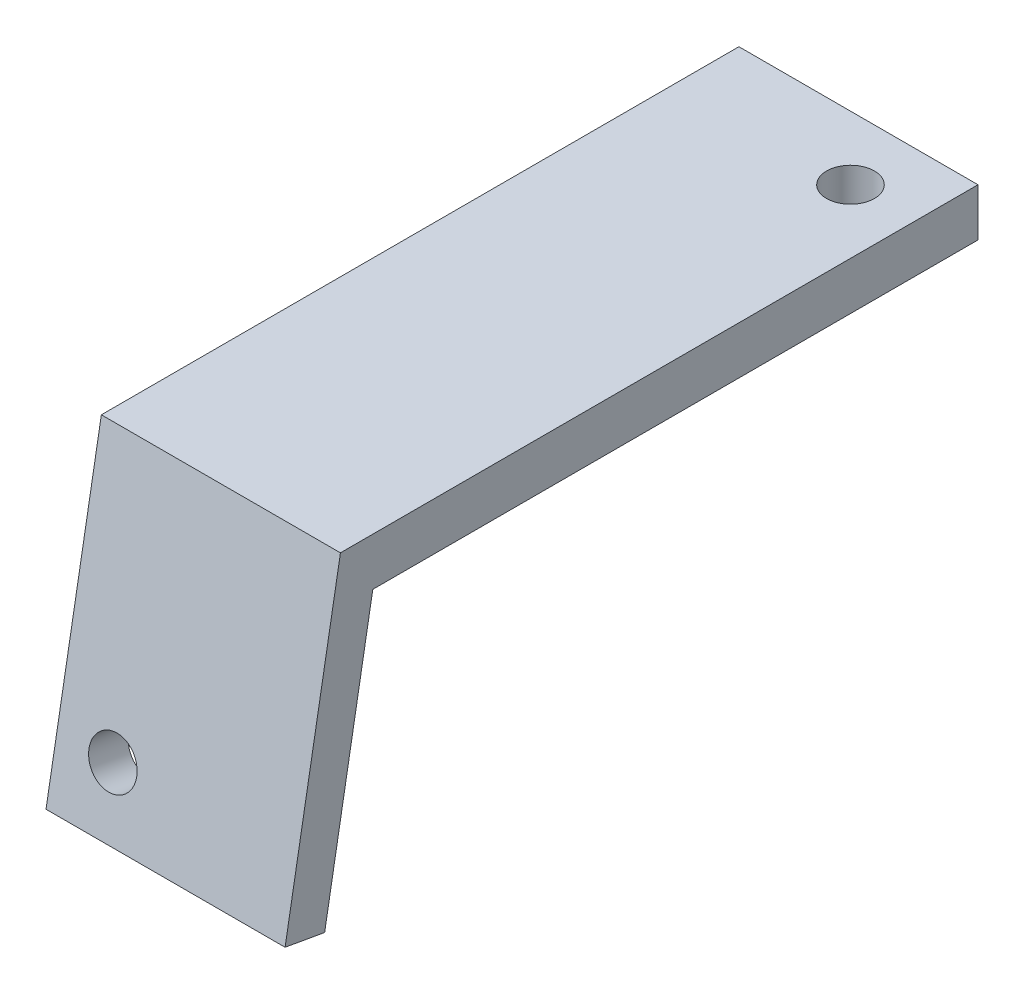
SolidWorks part; units mm, degrees
ref_plane "Front Plane" through (0, 0, 0) normal (0, 0, 1) x (1, 0, 0)
ref_plane "Top Plane" through (0, 0, 0) normal (0, 1, 0) x (1, 0, 0)
ref_plane "Right Plane" through (0, 0, 0) normal (1, 0, 0) x (0, 0, -1)
sketch "Sketch1" plane through (0, 0, 0) normal (0, 1, 0) x (1, 0, 0)
  line L1 (-7.5, -20) -> (7.5, -20)
  line L2 (-7.5, -20) -> (-7.5, 20)
  line L3 (-7.5, 20) -> (7.5, 20)
  line L4 (7.5, -20) -> (7.5, 20)
  line L5 (-7.5, -20) -> (7.5, 20) construction
  line L6 (-7.5, 20) -> (7.5, -20) construction
  circle A0 centre (3.5, 16) radius 1.5
  point P0 (0, 0)
  dimension "D3" = 3
  dimension "D1" = 15
  dimension "D2" = 40
  dimension "D4" = 4
  dimension "D5" = 4
extrude "Boss-Extrude1" add sketch "Sketch1" along normal blind 3
ref_plane "Plane1" through (0, -0.5107, 0.09) normal (0, 0.9848, -0.1736) x (1, 0, 0)
sketch "Sketch2" plane through (0, -0.5107, 0.09) normal (0, 0.9848, -0.1736) x (1, 0, 0)
  line L0 (-7.5, -20.2171) -> (-7.5, -19.6962) construction
  line L1 (-7.5, -17.6962) -> (7.5, -17.6962)
  line L2 (-7.5, -17.6962) -> (-7.5, -20.2171)
  line L3 (-7.5, -20.2171) -> (7.5, -20.2171)
  line L4 (7.5, -17.6962) -> (7.5, -20.2171)
  line L6 (-7.5, -19.6962) -> (7.5, -19.6962) construction
  dimension "D1" = 2
extrude "Boss-Extrude2" add sketch "Sketch2" against normal blind 20
sketch "Sketch3" plane through (0, 3.5107, 19.91) normal (0, 0.1736, 0.9848) x (1, 0, 0)
  line L1 (-7.5, -20.5185) -> (7.5, -20.5185) construction
  circle A0 centre (-4, -16.5185) radius 1.5
  ellipse E0 centre (3.5, 5.7328) end of major axis (5, 5.7328) minor radius 0.2605 construction
  dimension "D1" = 3
  dimension "D2" = 4
  dimension "D3" = 7.5
extrude "Cut-Extrude1" cut sketch "Sketch3" against normal blind 10
